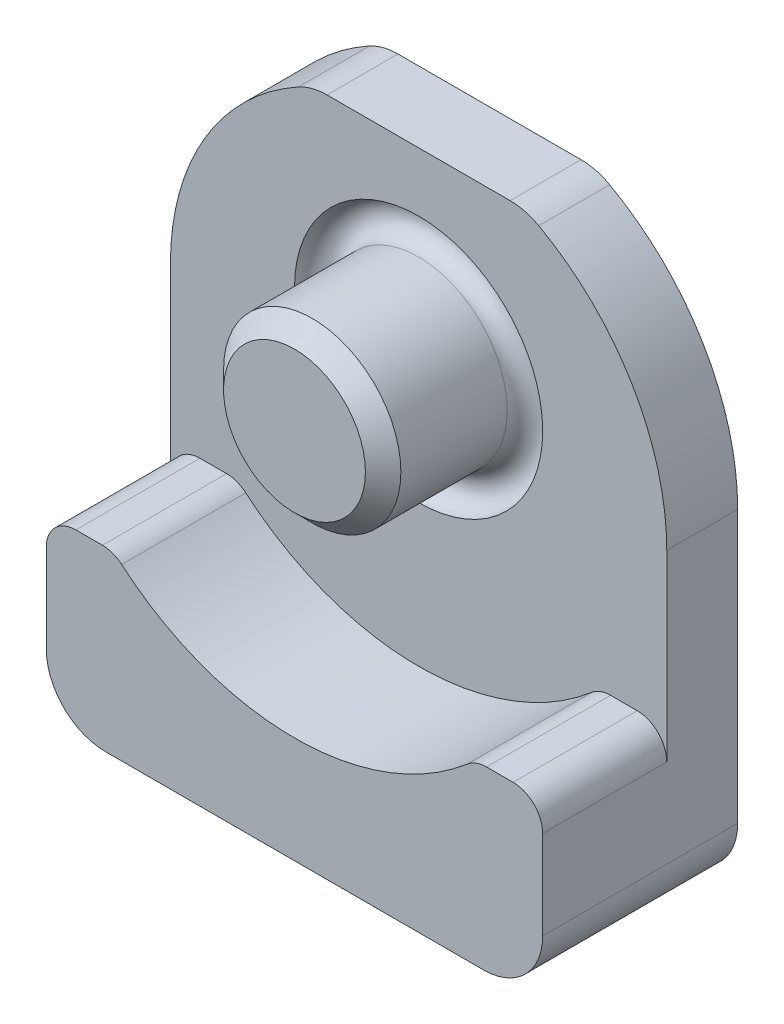
SolidWorks part; units mm, degrees
ref_plane "Front" through (0, 0, 0) normal (0, 0, 1) x (1, 0, 0)
ref_plane "Top" through (0, 0, 0) normal (0, 1, 0) x (1, 0, 0)
ref_plane "Right" through (0, 0, 0) normal (1, 0, 0) x (0, 0, -1)
sketch "Sketch1" plane through (0, 0, 0) normal (0, 0, 1) x (1, 0, 0)
  line L0 (4.2, -0.4) -> (4.2, -6)
  line L1 (4.2, -6) -> (-4.2, -6)
  line L2 (-4.2, -6) -> (-4.2, -0.4)
  arc A4 (4.2, -0.4) -> (-4.2, -0.4) centre (0, -0.4) ccw
  arc A5 (4.2, -0.4) -> (-4.2, -0.4) centre (0, -0.4) ccw
  dimension "D2" = 6
  dimension "D1" = 0.2
extrude "Basic" add sketch "Sketch1" along normal blind 3.3
sketch "Sketch2" plane through (0, 0, 3.3) normal (0, 0, 1) x (1, 0, 0)
  line L0 (4.2, -0.4) -> (4.2, -6) construction
  line L1 (-4.2, -6) -> (4.2, -6) construction
  line L2 (-4.2, -6) -> (-4.2, -3) construction
  line L3 (-4.2, -3) -> (-3.0594, -3)
  line L4 (4.2, -6) -> (4.2, -3) construction
  line L5 (3.0594, -3) -> (4.2, -3)
  line L6 (-4.2, -0.4) -> (-4.2, -6) construction
  line L7 (4.2, -6) -> (4.2, -0.4) construction
  line L8 (-4.2, -0.4) -> (-4.2, -3)
  line L9 (4.2, -3) -> (4.2, -0.4)
  circle A0 centre (0, 0.3) radius 1.5
  arc A1 (-3.0594, -3) -> (3.0594, -3) centre (0, 0.3) ccw
  arc A2 (4.2, -0.4) -> (-4.2, -0.4) centre (0, -0.4) ccw construction
  arc A3 (4.2, -0.4) -> (-4.2, -0.4) centre (0, -0.4) ccw
  circle A4 centre (0, 0.3) radius 4 construction
  dimension "D1" = 3
  dimension "D2" = 4.5
  dimension "D6" = 8
  dimension "D7" = 0.5
  dimension "D3" = 3
  dimension "D4" = 1.1406
  dimension "D5" = 0.3
extrude "Bearing Clearance" cut sketch "Sketch2" against normal offset from surface (2.1 mm away) 1.2 up to face at (0, -2.15, 0)
sketch "Sketch3" plane through (0, 0, 1.2) normal (0, 0, 1) x (1, 0, 0)
  line L0 (-1.7889, 3.4) -> (1.7889, 3.4)
  arc A0 (4.2, -0.4) -> (-4.2, -0.4) centre (0, -0.4) ccw construction
  arc A1 (1.7889, 3.4) -> (-1.7889, 3.4) centre (0, -0.4) ccw
  dimension "D2" = 0.4
  dimension "D1" = 3.4
extrude "Top Clearance" cut sketch "Sketch3" against normal through all
sketch "Sketch Position Bearing" plane through (0, 0, 1.2) normal (0, 0, 1) x (1, 0, 0)
  line L0 (0, -4.2) -> (0, -3.7)
  circle A0 centre (0, 0.3) radius 4
  arc A1 (-3.0594, -3) -> (3.0594, -3) centre (0, 0.3) ccw construction
  dimension "D1" = 8
sketch "Sketch7" plane through (0, 0, 0) normal (1, 0, 0) x (0, 0, -1)
  line L0 (-1.2, 3.4) -> (-1.2, -0.4) construction
  line L1 (-1.2, 1.8) -> (-3.3, 1.8) construction
  line L2 (-1.2, 1.8) -> (-1.2, 2.4)
  line L3 (-3.3, 0.3) -> (0, 0.3) construction
  line L4 (-3.3, 1.8) -> (-3.3, -1.2) construction
  line L5 (0, -0.4) -> (0, 3.4) construction
  arc A0 (-1.2, 1.8) -> (-1.2, 2.4) centre (-1.2, 2.1) ccw
  dimension "D1" = 0.3
revolve "Bearing Get Low" cut sketch "Sketch7" angle 360 about L3
fillet "R1" radius 1 4 edges at (-4.2, -6, 1.65) (4.2, -6, 1.65) (1.7889, 3.4, 0.6) (-1.7889, 3.4, 0.6)
fillet "R0.5" radius 0.5 4 edges at (4.2, -3, 2.25) (3.0594, -3, 2.25) (-4.2, -3, 2.25) (-3.0594, -3, 2.25)
chamfer "R0.3×45°" distance 0.3 angle 45 1 edges at (1.5, 0.3, 3.3)
